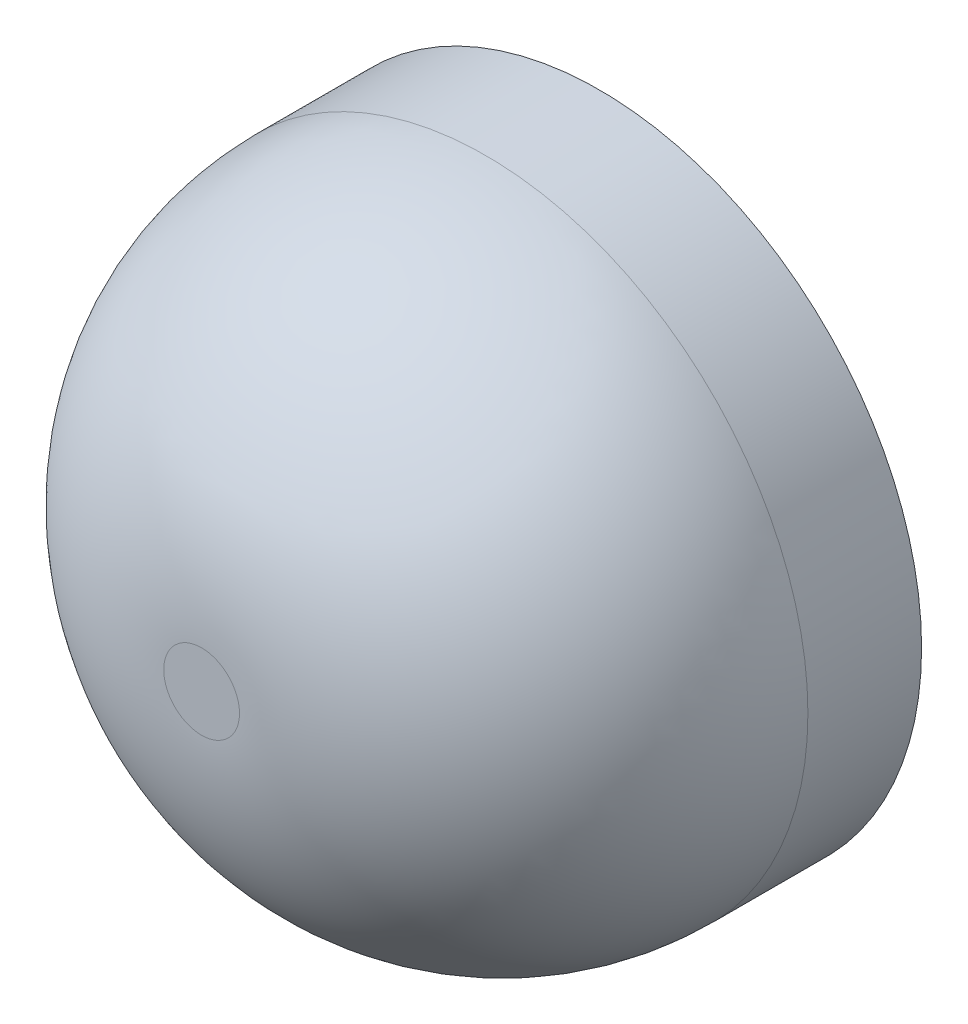
SolidWorks part; units mm, degrees
material "moto_glass_red"
ref_plane "Front Plane" through (0, 0, 0) normal (0, 0, 1) x (1, 0, 0)
ref_plane "Top Plane" through (0, 0, 0) normal (0, 1, 0) x (1, 0, 0)
ref_plane "Right Plane" through (0, 0, 0) normal (1, 0, 0) x (0, 0, -1)
sketch "Sketch1" plane through (0, 0, 0) normal (0, 0, 1) x (1, 0, 0)
  circle A0 centre (0, 0) radius 17
  dimension "D1" = 34
extrude "Boss-Extrude1" add sketch "Sketch1" along normal blind 21
fillet "Fillet1" radius 15 1 edges at (17, 0, 21)
shell "Shell1" thickness 1
